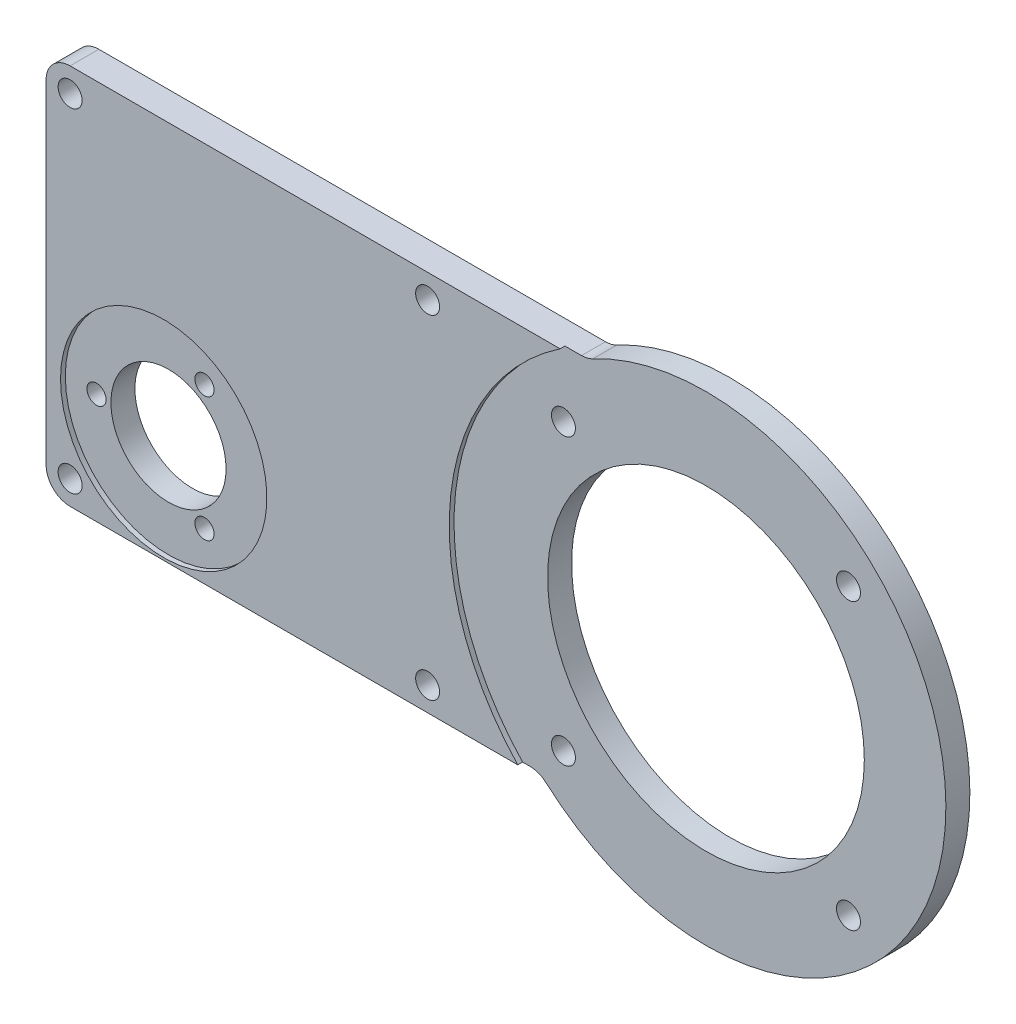
SolidWorks part; units mm, degrees
material "Acier allié inoxydable"
ref_plane "Plan de face" through (0, 0, 0) normal (0, 0, 1) x (1, 0, 0)
ref_plane "Plan de dessus" through (0, 0, 0) normal (0, 1, 0) x (1, 0, 0)
ref_plane "Plan de droite" through (0, 0, 0) normal (1, 0, 0) x (0, 0, -1)
ref_plane "Plan4" through (0, 0, 0) normal (0, 0, -1) x (-1, 0, 0)
sketch "Esquisse1" plane through (0, 0, 0) normal (0, 0, -1) x (-1, 0, 0)
  line L0 (73.3212, -72) -> (263, -72)
  line L1 (273, -62) -> (273, 77)
  line L2 (263, 87) -> (51.8748, 87)
  arc A0 (47.159, 88.1818) -> (66.6556, -74.5455) centre (0, 0) ccw
  arc A1 (66.6556, -74.5455) -> (73.3212, -72) centre (73.3212, -82) cw
  arc A2 (263, -72) -> (273, -62) centre (263, -62) ccw
  arc A3 (273, 77) -> (263, 87) centre (263, 77) ccw
  arc A4 (51.8748, 87) -> (47.159, 88.1818) centre (51.8748, 97) cw
extrude "Extrusion1" add sketch "Esquisse1" against normal blind 12
sketch "Esquisse2" plane through (0, 0, 12) normal (0, 0, 1) x (1, 0, 0)
  line L0 (-51.8748, 87) -> (-58.7878, 87)
  line L1 (-76.4264, -72) -> (-73.3212, -72)
  arc A0 (-47.159, 88.1818) -> (-51.8748, 87) centre (-51.8748, 97) cw
  arc A1 (-58.7878, 87) -> (-76.4264, -72) centre (0, 0) ccw
  arc A2 (-73.3212, -72) -> (-66.6556, -74.5455) centre (-73.3212, -82) cw
  arc A3 (-66.6556, -74.5455) -> (-47.159, 88.1818) centre (0, 0) ccw
extrude "Enlèv. mat.-Extru.1" cut sketch "Esquisse2" against normal blind 2
sketch "Esquisse3" plane through (0, 0, 12) normal (0, 0, 1) x (1, 0, 0)
  circle A0 centre (-224, -28) radius 43
extrude "Enlèv. mat.-Extru.2" cut sketch "Esquisse3" against normal blind 2
hole_wizard "Diamètre du perçage M10.0 (10)1" positions "Esquisse5" profile "Esquisse4" hole size "M10.0" standard "Ansi Métrique"
sketch "Esquisse5" plane through (0, 0, 10) normal (0, 0, 1) x (1, 0, 0)
  point P0 (59.397, -59.397)
sketch "Esquisse4" plane through (59.397, -59.397, 10) normal (1, 0, 0) x (0, -1, 0)
  line L0 (0, 0) -> (0, 10)
  line L1 (0, 10) -> (5, 10)
  line L2 (5, 10) -> (5, 0)
  line L5 (5, 0) -> (0, 0)
  line L11 (0, -6.35) -> (0, 107.95) construction
  dimension "Diamètre du perçage jusqu'au prochain" = 10
  dimension "Profondeur du perçage jusqu'au prochain" = 10
hole_wizard "Diamètre du perçage M10.0 (10)2" positions "Esquisse7" profile "Esquisse6" hole size "M10.0" standard "Ansi Métrique"
sketch "Esquisse7" plane through (0, 0, 10) normal (0, 0, 1) x (1, 0, 0)
  point P0 (59.397, 59.397)
sketch "Esquisse6" plane through (59.397, 59.397, 10) normal (1, 0, 0) x (0, -1, 0)
  line L0 (0, 0) -> (0, 10)
  line L1 (0, 10) -> (5, 10)
  line L2 (5, 10) -> (5, 0)
  line L5 (5, 0) -> (0, 0)
  line L11 (0, -6.35) -> (0, 107.95) construction
  dimension "Diamètre du perçage jusqu'au prochain" = 10
  dimension "Profondeur du perçage jusqu'au prochain" = 10
hole_wizard "Diamètre du perçage M10.0 (10)3" positions "Esquisse9" profile "Esquisse8" hole size "M10.0" standard "Ansi Métrique"
sketch "Esquisse9" plane through (0, 0, 12) normal (0, 0, 1) x (1, 0, 0)
  point P0 (-114, 77)
sketch "Esquisse8" plane through (-114, 77, 12) normal (1, 0, 0) x (0, -1, 0)
  line L0 (0, 0) -> (0, 12)
  line L1 (0, 12) -> (5, 12)
  line L2 (5, 12) -> (5, 0)
  line L5 (5, 0) -> (0, 0)
  line L11 (0, -6.35) -> (0, 107.95) construction
  dimension "Diamètre du perçage jusqu'au prochain" = 10
  dimension "Profondeur du perçage jusqu'au prochain" = 12
hole_wizard "Diamètre du perçage M10.0 (10)4" positions "Esquisse11" profile "Esquisse10" hole size "M10.0" standard "Ansi Métrique"
sketch "Esquisse11" plane through (0, 0, 10) normal (0, 0, 1) x (1, 0, 0)
  point P0 (-59.397, 59.397)
sketch "Esquisse10" plane through (-59.397, 59.397, 10) normal (1, 0, 0) x (0, -1, 0)
  line L0 (0, 0) -> (0, 10)
  line L1 (0, 10) -> (5, 10)
  line L2 (5, 10) -> (5, 0)
  line L5 (5, 0) -> (0, 0)
  line L11 (0, -6.35) -> (0, 107.95) construction
  dimension "Diamètre du perçage jusqu'au prochain" = 10
  dimension "Profondeur du perçage jusqu'au prochain" = 10
hole_wizard "Perçage1" positions "Esquisse13" profile "Esquisse12" legacy
sketch "Esquisse13" plane through (0, 0, 10) normal (0, 0, 1) x (1, 0, 0)
  point P0 (0, 0)
sketch "Esquisse12" plane through (0, 0, 10) normal (1, 0, 0) x (0, -1, 0)
  line L0 (0, 0) -> (0, 10)
  line L1 (0, 10) -> (66, 10)
  line L2 (66, 10) -> (66, 0)
  line L3 (66, 0) -> (0, 0)
  line L4 (0, 110) -> (0, -10) construction
  dimension "Diamètre" = 132
  dimension "Profondeur" = 10
hole_wizard "Diamètre du perçage M10.0 (10)5" positions "Esquisse15" profile "Esquisse14" hole size "M10.0" standard "Ansi Métrique"
sketch "Esquisse15" plane through (0, 0, 10) normal (0, 0, 1) x (1, 0, 0)
  point P0 (-59.397, -59.397)
sketch "Esquisse14" plane through (-59.397, -59.397, 10) normal (1, 0, 0) x (0, -1, 0)
  line L0 (0, 0) -> (0, 10)
  line L1 (0, 10) -> (5, 10)
  line L2 (5, 10) -> (5, 0)
  line L5 (5, 0) -> (0, 0)
  line L11 (0, -6.35) -> (0, 107.95) construction
  dimension "Diamètre du perçage jusqu'au prochain" = 10
  dimension "Profondeur du perçage jusqu'au prochain" = 10
hole_wizard "Diamètre du perçage M10.0 (10)6" positions "Esquisse17" profile "Esquisse16" hole size "M10.0" standard "Ansi Métrique"
sketch "Esquisse17" plane through (0, 0, 12) normal (0, 0, 1) x (1, 0, 0)
  point P0 (-114, -62)
sketch "Esquisse16" plane through (-114, -62, 12) normal (1, 0, 0) x (0, -1, 0)
  line L0 (0, 0) -> (0, 12)
  line L1 (0, 12) -> (5, 12)
  line L2 (5, 12) -> (5, 0)
  line L5 (5, 0) -> (0, 0)
  line L11 (0, -6.35) -> (0, 107.95) construction
  dimension "Diamètre du perçage jusqu'au prochain" = 10
  dimension "Profondeur du perçage jusqu'au prochain" = 12
hole_wizard "Diamètre du perçage M8.0 (8)1" positions "Esquisse19" profile "Esquisse18" hole size "M8.0" standard "Ansi Métrique"
sketch "Esquisse19" plane through (0, 0, 10) normal (0, 0, 1) x (1, 0, 0)
  point P0 (-209, -2.0192)
sketch "Esquisse18" plane through (-209, -2.0192, 10) normal (1, 0, 0) x (0, -1, 0)
  line L0 (0, 0) -> (0, 10)
  line L1 (0, 10) -> (4, 10)
  line L2 (4, 10) -> (4, 0)
  line L5 (4, 0) -> (0, 0)
  line L11 (0, -6.35) -> (0, 107.95) construction
  dimension "Diamètre du perçage jusqu'au prochain" = 8
  dimension "Profondeur du perçage jusqu'au prochain" = 10
hole_wizard "Diamètre du perçage M8.0 (8)2" positions "Esquisse21" profile "Esquisse20" hole size "M8.0" standard "Ansi Métrique"
sketch "Esquisse21" plane through (0, 0, 10) normal (0, 0, 1) x (1, 0, 0)
  point P0 (-254, -28)
sketch "Esquisse20" plane through (-254, -28, 10) normal (1, 0, 0) x (0, -1, 0)
  line L0 (0, 0) -> (0, 10)
  line L1 (0, 10) -> (4, 10)
  line L2 (4, 10) -> (4, 0)
  line L5 (4, 0) -> (0, 0)
  line L11 (0, -6.35) -> (0, 107.95) construction
  dimension "Diamètre du perçage jusqu'au prochain" = 8
  dimension "Profondeur du perçage jusqu'au prochain" = 10
hole_wizard "Diamètre du perçage M8.0 (8)3" positions "Esquisse23" profile "Esquisse22" hole size "M8.0" standard "Ansi Métrique"
sketch "Esquisse23" plane through (0, 0, 10) normal (0, 0, 1) x (1, 0, 0)
  point P0 (-209, -53.9808)
sketch "Esquisse22" plane through (-209, -53.9808, 10) normal (1, 0, 0) x (0, -1, 0)
  line L0 (0, 0) -> (0, 10)
  line L1 (0, 10) -> (4, 10)
  line L2 (4, 10) -> (4, 0)
  line L5 (4, 0) -> (0, 0)
  line L11 (0, -6.35) -> (0, 107.95) construction
  dimension "Diamètre du perçage jusqu'au prochain" = 8
  dimension "Profondeur du perçage jusqu'au prochain" = 10
hole_wizard "Dégagement M421" positions "Esquisse25" profile "Esquisse24" hole size "M42" standard "Ansi Métrique"
sketch "Esquisse25" plane through (0, 0, 10) normal (0, 0, 1) x (1, 0, 0)
  point P0 (-224, -28)
sketch "Esquisse24" plane through (-224, -28, 10) normal (1, 0, 0) x (0, -1, 0)
  line L0 (0, 0) -> (0, 10)
  line L1 (0, 10) -> (24, 10)
  line L2 (24, 10) -> (24, 0)
  line L5 (24, 0) -> (0, 0)
  line L11 (0, -6.35) -> (0, 107.95) construction
  dimension "Diamètre du perçage jusqu'au prochain" = 48
  dimension "Profondeur du perçage jusqu'au prochain" = 10
hole_wizard "Diamètre du perçage M10.0 (10)7" positions "Esquisse27" profile "Esquisse26" hole size "M10.0" standard "Ansi Métrique"
sketch "Esquisse27" plane through (0, 0, 12) normal (0, 0, 1) x (1, 0, 0)
  point P0 (-263, -62)
sketch "Esquisse26" plane through (-263, -62, 12) normal (1, 0, 0) x (0, -1, 0)
  line L0 (0, 0) -> (0, 12)
  line L1 (0, 12) -> (5, 12)
  line L2 (5, 12) -> (5, 0)
  line L5 (5, 0) -> (0, 0)
  line L11 (0, -6.35) -> (0, 107.95) construction
  dimension "Diamètre du perçage jusqu'au prochain" = 10
  dimension "Profondeur du perçage jusqu'au prochain" = 12
hole_wizard "Diamètre du perçage M10.0 (10)8" positions "Esquisse29" profile "Esquisse28" hole size "M10.0" standard "Ansi Métrique"
sketch "Esquisse29" plane through (0, 0, 12) normal (0, 0, 1) x (1, 0, 0)
  point P0 (-263, 77)
sketch "Esquisse28" plane through (-263, 77, 12) normal (1, 0, 0) x (0, -1, 0)
  line L0 (0, 0) -> (0, 12)
  line L1 (0, 12) -> (5, 12)
  line L2 (5, 12) -> (5, 0)
  line L5 (5, 0) -> (0, 0)
  line L11 (0, -6.35) -> (0, 107.95) construction
  dimension "Diamètre du perçage jusqu'au prochain" = 10
  dimension "Profondeur du perçage jusqu'au prochain" = 12
